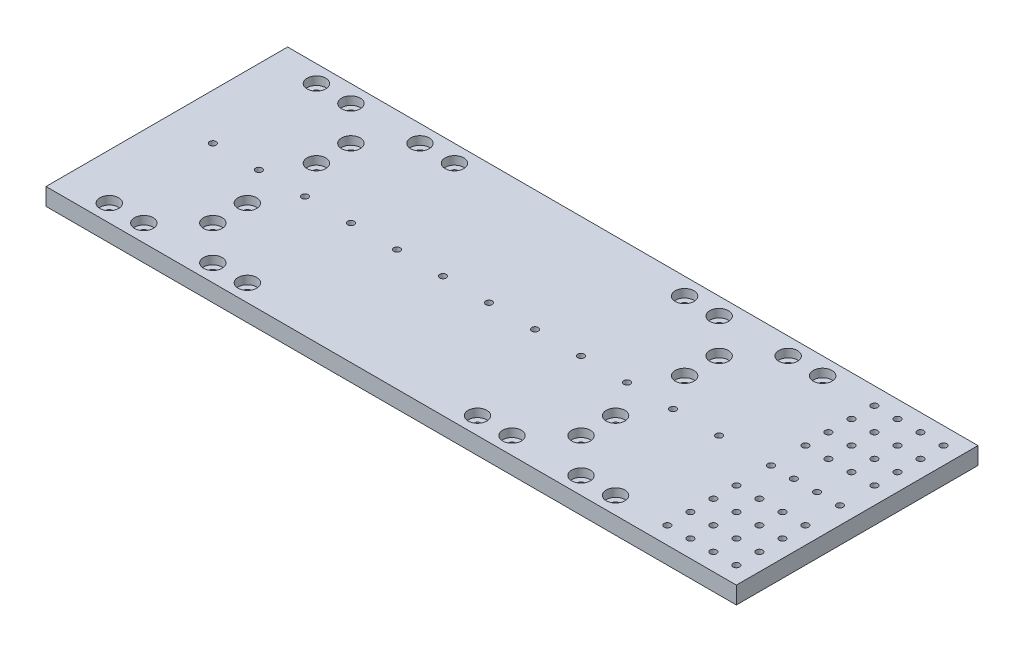
SolidWorks part; units mm, degrees
ref_plane "Front Plane" through (0, 0, 0) normal (0, 0, 1) x (1, 0, 0)
ref_plane "Top Plane" through (0, 0, 0) normal (0, 1, 0) x (1, 0, 0)
ref_plane "Right Plane" through (0, 0, 0) normal (1, 0, 0) x (0, 0, -1)
sketch "Sketch1" plane through (0, 0, 0) normal (0, 1, 0) x (1, 0, 0)
  line L1 (-381, -133.35) -> (381, -133.35)
  line L2 (-381, -133.35) -> (-381, 133.35)
  line L3 (-381, 133.35) -> (381, 133.35)
  line L4 (381, -133.35) -> (381, 133.35)
  line L5 (-381, -133.35) -> (381, 133.35) construction
  line L6 (-381, 133.35) -> (381, -133.35) construction
  point P0 (0, 0)
  dimension "D1" = 266.7
  dimension "D2" = 762
extrude "Boss-Extrude1" add sketch "Sketch1" along normal blind 19.05
hole_wizard "CBORE for 5/16 Hex Head Bolt1" positions "Sketch6" profile "Sketch7" counterbore size "5/16" standard "ANSI Inch" end condition through all
sketch "Sketch6" plane through (0, 19.05, 0) normal (0, 1, 0) x (1, 0, 0)
  line L0 (381, 133.35) -> (-381, 133.35) construction
  line L1 (-381, 133.35) -> (-381, -133.35) construction
  line L2 (0, 0) -> (-381, 0) construction
  point P0 (-330.2, 114.3)
  point P2 (-292.1, 114.3)
  point P4 (-254, 76.2)
  point P6 (-254, 38.1)
  point P8 (-215.9, 114.3)
  point P10 (-177.8, 114.3)
  point P26 (76.2, 114.3)
  point P27 (114.3, 114.3)
  point P28 (152.4, 76.2)
  point P29 (152.4, 38.1)
  point P30 (190.5, 114.3)
  point P31 (228.6, 114.3)
  point P37 (228.6, -114.3)
  point P38 (190.5, -114.3)
  point P39 (152.4, -38.1)
  point P40 (152.4, -76.2)
  point P41 (114.3, -114.3)
  point P42 (76.2, -114.3)
  point P43 (-177.8, -114.3)
  point P44 (-215.9, -114.3)
  point P45 (-254, -38.1)
  point P46 (-254, -76.2)
  point P47 (-292.1, -114.3)
  point P48 (-330.2, -114.3)
  dimension "D1" = 38.1
  dimension "D2" = 38.1
  dimension "D3" = 76.2
  dimension "D4" = 38.1
  dimension "D5" = 19.05
  dimension "D6" = 50.8
  dimension "D7" = 38.1
  dimension "D8" = 38.1
  dimension "D10" = 406.4
  dimension "D9" = 2
sketch "Sketch7" plane through (-330.2, 19.05, -114.3) normal (1, 0, 0) x (0, 0, 1)
  line L0 (0, 0) -> (0, 19.05)
  line L1 (0, 19.05) -> (4.2164, 19.05)
  line L3 (4.2164, 19.05) -> (4.2164, 9.144)
  line L4 (4.2164, 9.144) -> (10.3187, 9.144)
  line L5 (10.3187, 9.144) -> (10.3187, 0)
  line L7 (10.3187, 0) -> (0, 0)
  line L11 (0, -6.35) -> (0, 107.95) construction
  dimension "Thru Hole Dia." = 8.4328
  dimension "Thru Hole Depth" = 19.05
  dimension "C'Bore Dia." = 20.6375
  dimension "C'Bore Depth" = 9.144
hole_wizard "1/4 Clearance Hole1" positions "Sketch8" profile "Sketch10" hole size "1/4" standard "ANSI Inch"
sketch "Sketch8" plane through (0, 19.05, 0) normal (0, 1, 0) x (1, 0, 0)
  line L0 (-381, 133.35) -> (-381, -133.35) construction
  line L1 (381, 133.35) -> (-381, 133.35) construction
  line L2 (381, -133.35) -> (381, 133.35) construction
  point P2 (-330.2, 0)
  point P17 (-279.4, 0)
  point P18 (-228.6, 0)
  point P19 (-177.8, 0)
  point P20 (-127, 0)
  point P21 (-76.2, 0)
  point P22 (-25.4, 0)
  point P23 (25.4, 0)
  point P24 (76.2, 0)
  point P25 (127, 0)
  point P26 (177.8, 0)
  point P27 (228.6, 0)
  point P30 (330.2, 0) [skipped]
  point P31 (279.4, 0) [skipped]
  point P32 (361.95, 114.3)
  point P45 (336.55, 114.3)
  point P46 (311.15, 114.3)
  point P47 (285.75, 114.3)
  point P48 (336.55, 88.9)
  point P49 (311.15, 88.9)
  point P50 (285.75, 88.9)
  point P51 (336.55, 63.5)
  point P52 (311.15, 63.5)
  point P53 (285.75, 63.5)
  point P54 (336.55, 38.1)
  point P55 (311.15, 38.1)
  point P56 (285.75, 38.1)
  point P63 (336.55, -38.1)
  point P64 (311.15, -38.1)
  point P65 (285.75, -38.1)
  point P66 (336.55, -63.5)
  point P67 (311.15, -63.5)
  point P68 (285.75, -63.5)
  point P69 (336.55, -88.9)
  point P70 (311.15, -88.9)
  point P71 (285.75, -88.9)
  point P72 (336.55, -114.3)
  point P73 (311.15, -114.3)
  point P74 (285.75, -114.3)
  point P75 (361.95, 88.9)
  point P76 (361.95, 63.5)
  point P77 (361.95, 38.1)
  point P80 (361.95, -38.1)
  point P81 (361.95, -63.5)
  point P82 (361.95, -88.9)
  point P83 (361.95, -114.3)
  point P84 (361.95, -12.7) [skipped]
  point P85 (361.95, 12.7) [skipped]
  point P86 (285.75, -12.7) [skipped]
  point P87 (311.15, -12.7) [skipped]
  point P88 (336.55, -12.7) [skipped]
  point P89 (285.75, 12.7) [skipped]
  point P90 (311.15, 12.7) [skipped]
  point P91 (336.55, 12.7) [skipped]
  point P95 (361.95, 0)
  point P102 (336.55, 0)
  point P103 (311.15, 0)
  point P104 (285.75, 0)
  dimension "D1" = 50.8
  dimension "D2" = 19.05
  dimension "D3" = 19.05
sketch "Sketch10" plane through (-330.2, 19.05, 0) normal (1, 0, 0) x (0, 0, 1)
  line L0 (0, 0) -> (0, 19.05)
  line L1 (0, 19.05) -> (3.5712, 19.05)
  line L2 (3.5712, 19.05) -> (3.5712, 0)
  line L5 (3.5712, 0) -> (0, 0)
  line L11 (0, -6.35) -> (0, 107.95) construction
  dimension "Thru Hole Dia." = 7.1425
  dimension "Thru Hole Depth" = 19.05
